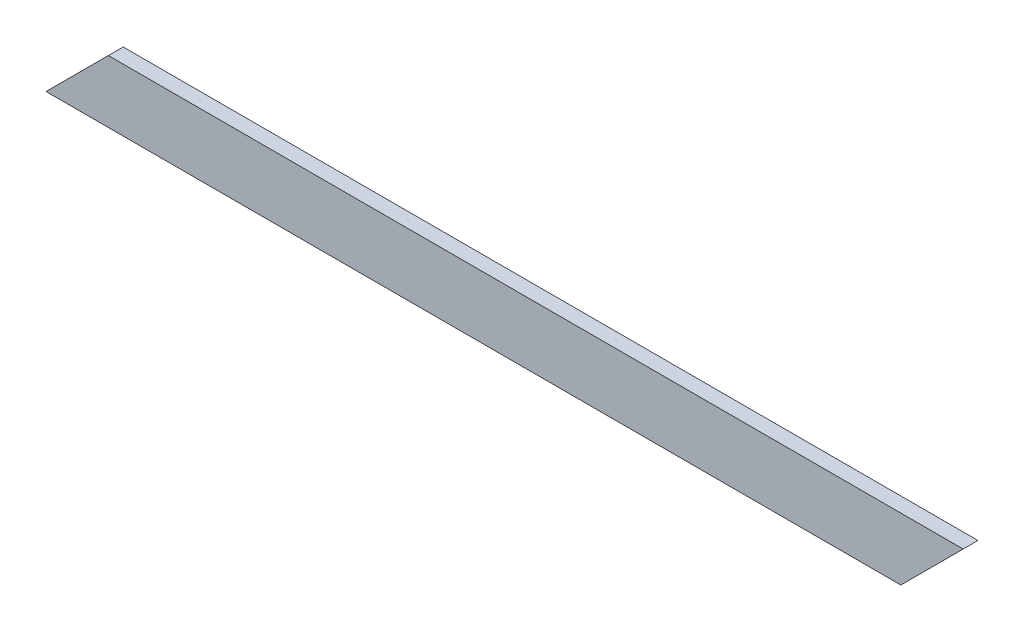
SolidWorks part; units mm, degrees
material "Glass"
ref_plane "Front Plane" through (0, 0, 0) normal (0, 0, 1) x (1, 0, 0)
ref_plane "Top Plane" through (0, 0, 0) normal (0, 1, 0) x (1, 0, 0)
ref_plane "Right Plane" through (0, 0, 0) normal (1, 0, 0) x (0, 0, -1)
sketch "Sketch4" plane through (0, 0, 0) normal (0, 0, 1) x (1, 0, 0)
  line L0 (0, 0) -> (3657.6, 0)
  line L1 (3657.6, 0) -> (3924.3, 266.7)
  line L2 (3924.3, 266.7) -> (266.7, 266.7)
  line L3 (266.7, 266.7) -> (0, 0)
extrude "Boss-Extrude3" add sketch "Sketch4" along normal blind 63.5
